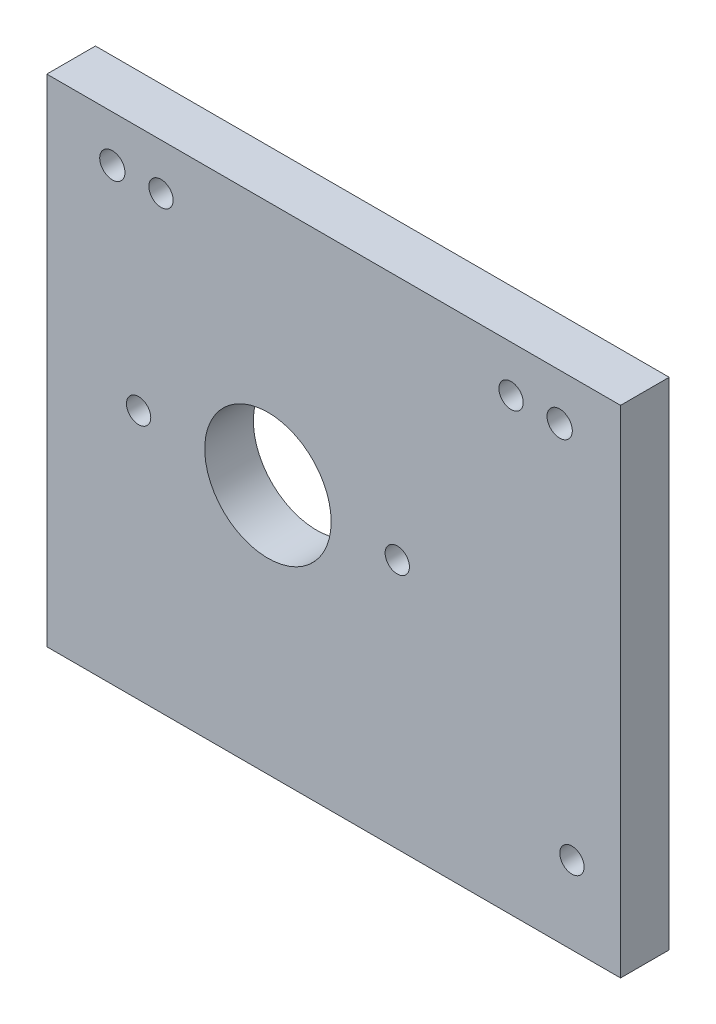
SolidWorks part; units mm, degrees
ref_plane "Alzado" through (0, 0, 0) normal (0, 0, 1) x (1, 0, 0)
ref_plane "Planta" through (0, 0, 0) normal (0, 1, 0) x (1, 0, 0)
ref_plane "Vista lateral" through (0, 0, 0) normal (1, 0, 0) x (0, 0, -1)
sketch "Croquis1" plane through (0, 0, 0) normal (0, 0, 1) x (1, 0, 0)
  line L0 (0, 0) -> (0, 20.5)
  line L5 (29.2611, -25.7476) -> (24.2611, -25.7476)
  line L6 (24.2611, -25.7476) -> (24.2611, -17.7476)
  line L7 (18, 20.5) -> (-18, 20.5)
  line L11 (-29.7389, -25.7476) -> (29.2611, -25.7476)
  line L12 (-29.7389, -25.7476) -> (-29.7389, 25.2524)
  line L13 (-29.7389, 25.2524) -> (29.2611, 25.2524)
  line L14 (29.2611, -25.7476) -> (29.2611, 25.2524)
  line L20 (-18, 20.5) -> (-23, 20.5)
  line L21 (18, 20.5) -> (23, 20.5)
  line L27 (-24.5, -17.5) -> (10.5, 17.5) construction
  line L28 (-24.5, 17.5) -> (10.5, -17.5) construction
  circle A3 centre (24.2611, -17.7476) radius 1.25
  circle A4 centre (-18, 20.5) radius 1.25
  circle A5 centre (18, 20.5) radius 1.25
  circle A9 centre (-23, 20.5) radius 1.3
  circle A10 centre (23, 20.5) radius 1.3
  circle A11 centre (-7, 0) radius 6.5
  circle A12 centre (-20.3, 0) radius 1.25
  circle A13 centre (6.3, 0) radius 1.25
  point P0 (0, 0)
  point P10 (0, 20.5)
  point P11 (-0.2389, 17.2524)
  point P22 (-7, 0)
  point P24 (-20.3, 0)
  point P27 (6.3, 0)
  dimension "D4" = 2.5
  dimension "D5" = 2.5
  dimension "D8" = 8
  dimension "D9" = 2.5
  dimension "D12" = 5
  dimension "D13" = 2.5
  dimension "D16" = 2.6
  dimension "D18" = 2.6
  dimension "D20" = 35
  dimension "D21" = 13
  dimension "D14" = 2.5
  dimension "D2" = 20.5
  dimension "D3" = 18
  dimension "D6" = 7
  dimension "D7" = 5
  dimension "D10" = 51
  dimension "D11" = 59
  dimension "D17" = 5
  dimension "D19" = 38.2476
extrude "Saliente-Extruir1" add sketch "Croquis1" along normal blind 5
